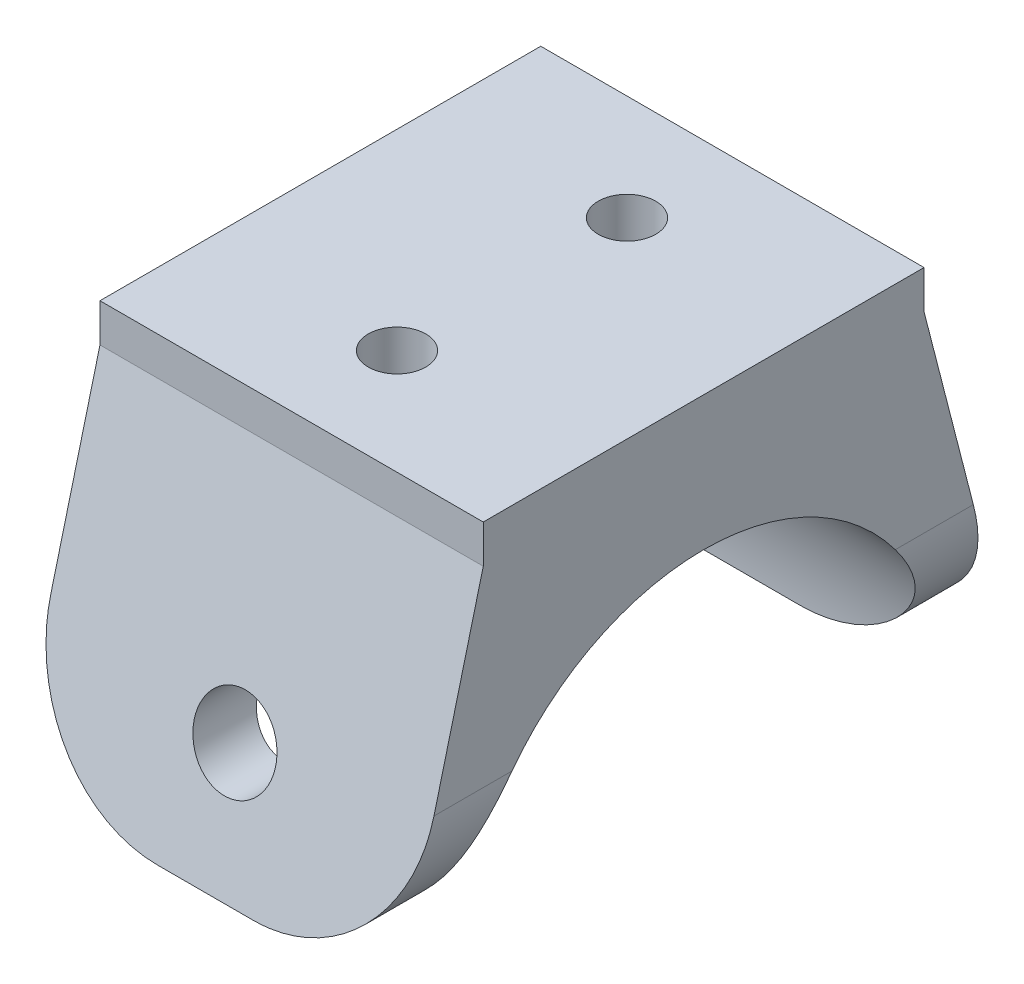
SolidWorks part; units mm, degrees
ref_plane "Front Plane" through (0, 0, 0) normal (0, 0, 1) x (1, 0, 0)
ref_plane "Top Plane" through (0, 0, 0) normal (0, 1, 0) x (1, 0, 0)
ref_plane "Right Plane" through (0, 0, 0) normal (1, 0, 0) x (0, 0, -1)
sketch "Sketch1" plane through (0, 0, 0) normal (0, 0, 1) x (1, 0, 0)
  line L1 (-5, -19.5) -> (5, -19.5)
  line L2 (-20, -4.5) -> (-20, 19.5)
  line L3 (-20, 19.5) -> (20, 19.5)
  line L4 (20, -4.5) -> (20, 19.5)
  line L5 (-20, -19.5) -> (20, 19.5) construction
  line L6 (-20, 19.5) -> (20, -19.5) construction
  circle A0 centre (0, -7.5) radius 4.25
  arc A1 (5, -19.5) -> (20, -4.5) centre (5, -4.5) ccw
  arc A2 (-5, -19.5) -> (-20, -4.5) centre (-5, -4.5) cw
  point P0 (0, 0)
  dimension "D3" = 27
  dimension "D4" = 15
  dimension "D1" = 40
  dimension "D2" = 39
extrude "Boss-Extrude1" add sketch "Sketch1" along normal mid plane 64
sketch "Sketch2" plane through (-20, 0, 0) normal (-1, 0, 0) x (0, 0, 1)
  line L0 (0, -21.45) -> (0, 21.45) construction
  line L1 (32, 19.5) -> (-32, 19.5) construction
  line L2 (23, 19.5) -> (23, 15.5)
  line L3 (23, 15.5) -> (32, -19.5)
  line L4 (32, -19.5) -> (32, 19.5)
  line L5 (32, 19.5) -> (23, 19.5)
  line L6 (-32, 19.5) -> (-23, 19.5)
  line L7 (-32, -19.5) -> (-32, 19.5)
  line L8 (-23, 15.5) -> (-32, -19.5)
  line L9 (-23, 19.5) -> (-23, 15.5)
extrude "Cut-Extrude1" cut sketch "Sketch2" against normal blind 64
sketch "Sketch3" plane through (0, 19.5, 0) normal (0, 1, 0) x (1, 0, 0)
  line L0 (-21.45, 0) -> (21.45, 0) construction
  circle A0 centre (0, 12) radius 3
  circle A1 centre (0, -12) radius 3
  dimension "D1" = 12
extrude "Cut-Extrude2" cut sketch "Sketch3" against normal blind 14
sketch "Sketch4" plane through (-20, 0, 0) normal (-1, 0, 0) x (0, 0, 1)
  line L0 (32, -19.5) -> (-32, -19.5) construction
  circle A0 centre (0, -19.5) radius 25
extrude "Cut-Extrude3" cut sketch "Sketch4" against normal through all
